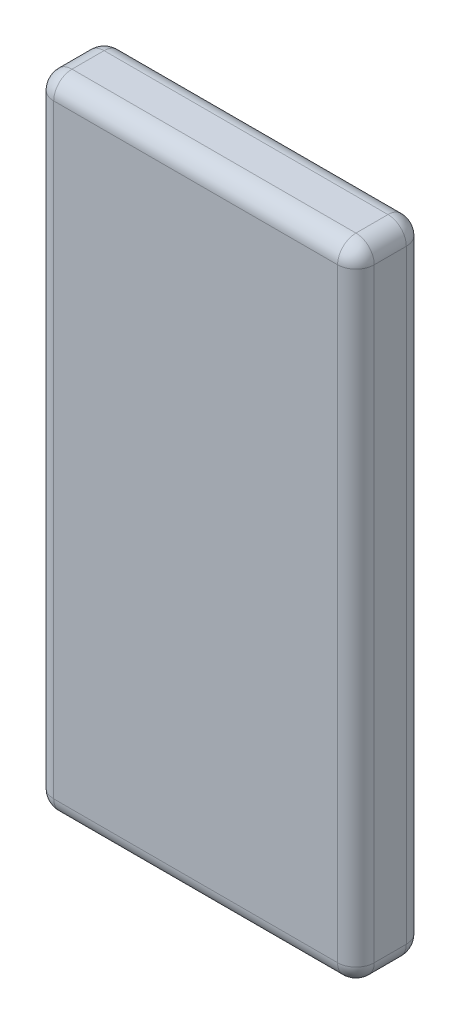
SolidWorks part; units mm, degrees
ref_plane "Front Plane" through (0, 0, 0) normal (0, 0, 1) x (1, 0, 0)
ref_plane "Top Plane" through (0, 0, 0) normal (0, 1, 0) x (1, 0, 0)
ref_plane "Right Plane" through (0, 0, 0) normal (1, 0, 0) x (0, 0, -1)
sketch "Esquisse1" plane through (0, 0, 0) normal (0, 0, 1) x (1, 0, 0)
  line L1 (0, 0) -> (-70, 0)
  line L2 (0, 0) -> (0, -140)
  line L3 (0, -140) -> (-70, -140)
  line L4 (-70, 0) -> (-70, -140)
  line L5 (-35, -140) -> (-35, 0) construction
  line L6 (0, -70) -> (-70, -70) construction
  point P80 (-35, -70)
  dimension "D1" = 140
  dimension "D2" = 70
extrude "Boss.-Extru.1" add sketch "Esquisse1" along normal blind 15
fillet "Congé1" radius 4 4 edges at (0, -140, 7.5) (-70, -140, 7.5) (-70, 0, 7.5) (0, 0, 7.5)
fillet "Congé2" radius 4 8 edges at (-68.8284, -138.8284, 15) (-70, -70, 15) (-68.8284, -1.1716, 15) (-35, 0, 15) (-1.1716, -1.1716, 15) (0, -70, 15) (-1.1716, -138.8284, 15) (-35, -140, 15)
fillet "Congé3" radius 4 8 edges at (-1.1716, -1.1716, 0) (-35, 0, 0) (-68.8284, -1.1716, 0) (-70, -70, 0) (-68.8284, -138.8284, 0) (-35, -140, 0) (-1.1716, -138.8284, 0) (0, -70, 0)
